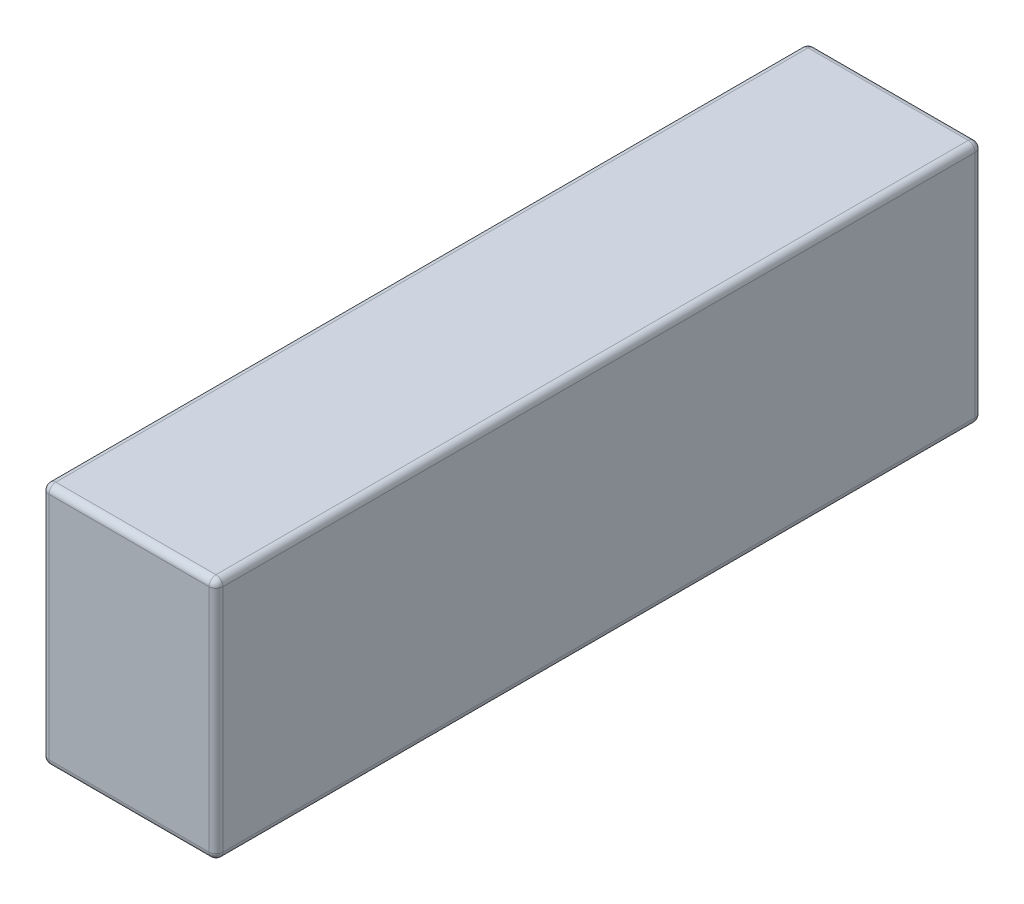
SolidWorks part; units mm, degrees
ref_plane "Front Plane" through (0, 0, 0) normal (0, 0, 1) x (1, 0, 0)
ref_plane "Top Plane" through (0, 0, 0) normal (0, 1, 0) x (1, 0, 0)
ref_plane "Right Plane" through (0, 0, 0) normal (1, 0, 0) x (0, 0, -1)
sketch "Sketch1" plane through (0, 0, 0) normal (0, 1, 0) x (1, 0, 0)
  line L1 (12.5, -55) -> (-12.5, -55)
  line L2 (12.5, -55) -> (12.5, 55)
  line L3 (12.5, 55) -> (-12.5, 55)
  line L4 (-12.5, -55) -> (-12.5, 55)
  line L5 (12.5, -55) -> (-12.5, 55) construction
  line L6 (12.5, 55) -> (-12.5, -55) construction
  point P0 (0, 0)
  dimension "D1" = 25
  dimension "D2" = 110
extrude "Boss-Extrude1" add sketch "Sketch1" along normal blind 35
fillet "Fillet1" radius 1 12 edges at (0, 0, -55) (-12.5, 17.5, -55) (-12.5, 0, 0) (-12.5, 17.5, 55) (0, 0, 55) (0, 35, -55) (0, 35, 55) (-12.5, 35, 0) (12.5, 17.5, 55) (12.5, 35, 0) (12.5, 17.5, -55) (12.5, 0, 0)
